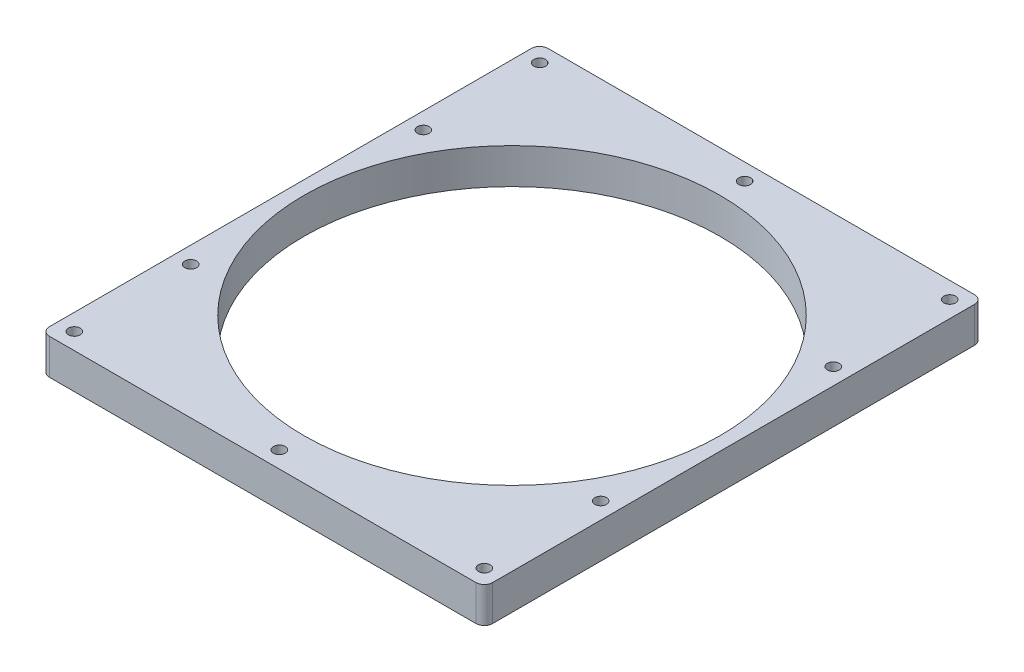
SolidWorks part; units mm, degrees
ref_plane "Front Plane" through (0, 0, 0) normal (0, 0, 1) x (1, 0, 0)
ref_plane "Top Plane" through (0, 0, 0) normal (0, 1, 0) x (1, 0, 0)
ref_plane "Right Plane" through (0, 0, 0) normal (1, 0, 0) x (0, 0, -1)
sketch "Sketch1" plane through (0, 0, 0) normal (0, 1, 0) x (1, 0, 0)
  line L0 (-80, 0) -> (80, 0) construction
  line L1 (-80, -90) -> (80, -90)
  line L2 (-80, -90) -> (-80, 90)
  line L3 (-80, 90) -> (80, 90)
  line L4 (80, -90) -> (80, 90)
  line L5 (-80, -90) -> (80, 90) construction
  line L6 (-80, 90) -> (80, -90) construction
  line L7 (0, 90) -> (0, -90) construction
  circle A0 centre (0, 0) radius 75.125
  circle A4 centre (-74, -84) radius 2.125
  circle A5 centre (-74, -42) radius 2.125
  circle A6 centre (-74, 84) radius 2.125
  circle A7 centre (74, -84) radius 2.125
  circle A8 centre (74, -42) radius 2.125
  circle A9 centre (74, 84) radius 2.125
  circle A10 centre (0, -84) radius 2.125
  circle A11 centre (0, 84) radius 2.125
  circle A13 centre (74, 42) radius 2.125
  circle A14 centre (-74, 42) radius 2.125
  point P0 (0, 0)
  point P16 (0, 0)
  dimension "D1" = 150.25
  dimension "D7" = 4.25
  dimension "D10" = 4.25
  dimension "D11" = 4.25
  dimension "D5" = 180
  dimension "D6" = 160
  dimension "D8" = 6
  dimension "D9" = 6
  dimension "D12" = 6
  dimension "D14" = 6
  dimension "42" = 42
extrude "Boss-Extrude1" add sketch "Sketch1" along normal blind 12.825
fillet "Fillet1" radius 3 4 edges at (-80, 6.4125, -90) (80, 6.4125, 90) (80, 6.4125, -90) (-80, 6.4125, 90)
